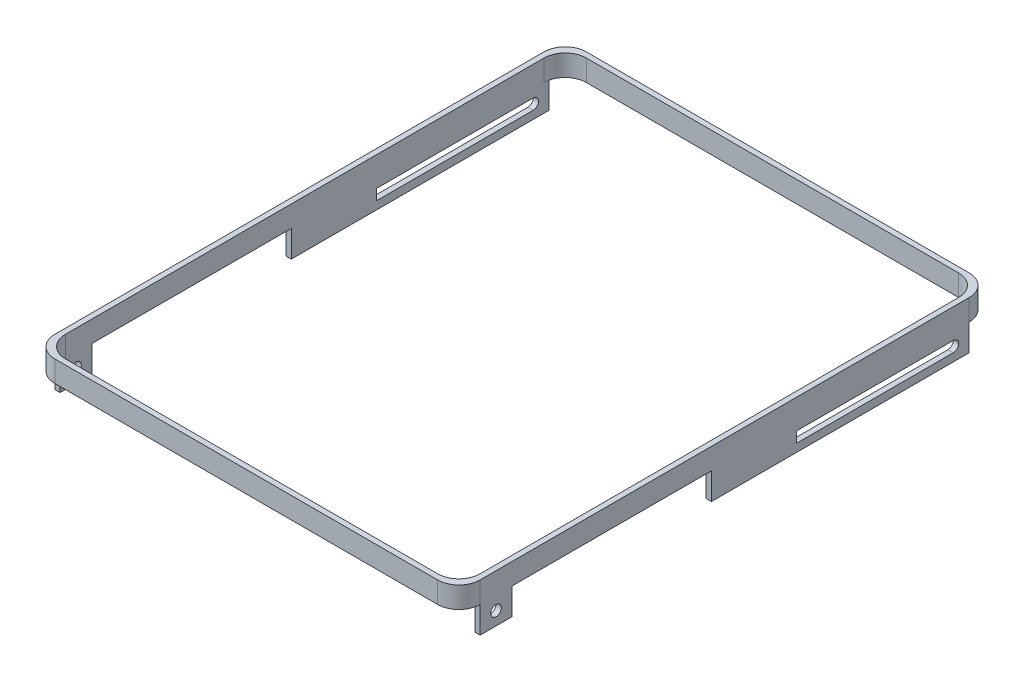
SolidWorks part; units mm, degrees
ref_plane "Front Plane" through (0, 0, 0) normal (0, 0, 1) x (1, 0, 0)
ref_plane "Top Plane" through (0, 0, 0) normal (0, 1, 0) x (1, 0, 0)
ref_plane "Right Plane" through (0, 0, 0) normal (1, 0, 0) x (0, 0, -1)
sketch "Sketch5" plane through (0, 0, 0) normal (0, 1, 0) x (1, 0, 0)
  line L1 (-180, 250) -> (180, 250)
  line L2 (-200, 230) -> (-200, -230)
  line L3 (-180, -250) -> (180, -250)
  line L4 (200, 230) -> (200, -230)
  line L5 (-200, 250) -> (200, -250) construction
  line L6 (-200, -250) -> (200, 250) construction
  arc A0 (-200, -230) -> (-180, -250) centre (-180, -230) ccw
  arc A1 (180, -250) -> (200, -230) centre (180, -230) ccw
  arc A2 (180, 250) -> (200, 230) centre (180, 230) cw
  arc A3 (-180, 250) -> (-200, 230) centre (-180, 230) ccw
  point P0 (0, 0)
  dimension "D3" = 20
  dimension "D1" = 500
  dimension "D2" = 400
extrude "Boss-Extrude2" add sketch "Sketch5" along normal blind 20
sketch "Sketch6" plane through (0, 20, 0) normal (0, 1, 0) x (1, 0, 0)
  line L1 (-175, -245) -> (175, -245)
  line L2 (-195, -225) -> (-195, 225)
  line L3 (-175, 245) -> (175, 245)
  line L4 (195, -225) -> (195, 225)
  line L5 (-195, -245) -> (195, 245) construction
  line L6 (-195, 245) -> (195, -245) construction
  arc A0 (-175, -245) -> (-195, -225) centre (-175, -225) cw
  arc A1 (175, -245) -> (195, -225) centre (175, -225) ccw
  arc A2 (175, 245) -> (195, 225) centre (175, 225) cw
  arc A3 (-195, 225) -> (-175, 245) centre (-175, 225) cw
  point P0 (0, 0)
  dimension "D3" = 20
  dimension "D1" = 490
  dimension "D2" = 390
extrude "Cut-Extrude1" cut sketch "Sketch6" against normal blind 20
sketch "Sketch7" plane through (200, 0, 0) normal (1, 0, 0) x (0, 0, -1)
  line L0 (230, 0) -> (230, -25)
  line L1 (230, -25) -> (-12.5565, -25)
  line L2 (-12.5565, -25) -> (-12.5565, 0)
  line L3 (-230, 0) -> (230, 0) construction
  line L4 (-12.5565, 0) -> (230, 0)
  dimension "D1" = 25
extrude "Boss-Extrude3" add sketch "Sketch7" against normal blind 5
sketch "Sketch8" plane through (-200, 0, 0) normal (-1, 0, 0) x (0, 0, 1)
  line L0 (-230, -25) -> (-230, 0) construction
  line L1 (12.5565, 0) -> (12.5565, -25) construction
  line L2 (12.5565, -25) -> (-230, -25) construction
  line L3 (-230, -25) -> (-230, 0)
  line L4 (12.5565, 0) -> (12.5565, -25)
  line L5 (12.5565, -25) -> (-230, -25)
  line L6 (-230, 0) -> (12.5565, 0)
extrude "Boss-Extrude4" add sketch "Sketch8" against normal blind 5
sketch "Sketch9" plane through (-200, 0, 0) normal (-1, 0, 0) x (0, 0, 1)
  line L0 (12.5565, 0) -> (-230, 0) construction
sketch "Sketch10" plane through (200, 0, 0) normal (1, 0, 0) x (0, 0, -1)
  line L10 (214.9751, -7.5) -> (2.4435, -7.5)
  line L13 (-12.5565, 0) -> (230, 0) construction
  line L15 (230, -25) -> (230, 0) construction
  line L16 (-12.5565, 0) -> (-12.5565, -25) construction
  line L18 (217.347, -16.9016) -> (215, -16.9016) construction
  line L20 (2.4435, -17.5) -> (214.9751, -17.5)
  arc A1 (2.4435, -7.5) -> (2.4435, -17.5) centre (2.4435, -12.5) ccw
  arc A3 (214.9751, -17.5) -> (214.9751, -7.5) centre (214.9751, -12.5) ccw
  dimension "D11" = 10
  dimension "D12" = 15.0249
  dimension "D14" = 5
  dimension "D13" = 15
  dimension "D15" = 212.5317
  dimension "D16" = 212.5317
extrude "Cut-Extrude2" cut sketch "Sketch10" against normal through all both and the other way through all
sketch "Sketch11" plane through (200, 0, 0) normal (1, 0, 0) x (0, 0, -1)
  line L0 (-230, 0) -> (-230, -25)
  line L1 (-230, -25) -> (-200, -25)
  line L2 (-200, -25) -> (-200, 0)
  line L3 (-230, 0) -> (-12.5565, 0) construction
  line L4 (-12.5565, -25) -> (-236.7643, -25) construction
  line L5 (-200, 0) -> (-230, 0)
  dimension "D1" = 30
  dimension "D2" = 25
extrude "Boss-Extrude5" add sketch "Sketch11" against normal blind 5
sketch "Sketch13" plane through (-200, 0, 0) normal (-1, 0, 0) x (0, 0, 1)
  line L0 (200, -25) -> (200, 0) construction
  line L1 (230, 0) -> (230, -25) construction
  line L2 (230, -25) -> (200, -25) construction
  line L3 (200, -25) -> (200, 0)
  line L4 (230, 0) -> (230, -25)
  line L5 (230, -25) -> (200, -25)
  line L6 (200, 0) -> (230, 0)
extrude "Boss-Extrude6" add sketch "Sketch13" against normal blind 5
sketch "Sketch14" plane through (-200, 0, 0) normal (-1, 0, 0) x (0, 0, 1)
  line L0 (-2.4435, -12.5) -> (215, -12.5) construction
  line L1 (230, -25) -> (230, 0) construction
  line L3 (12.5565, 0) -> (200, 0) construction
  line L5 (200, 0) -> (200, -25) construction
  line L6 (200, 0) -> (200, -25) construction
  circle A1 centre (215, -12.5) radius 5
  dimension "D2" = 10
  dimension "D1" = 15
extrude "Cut-Extrude3" cut sketch "Sketch14" against normal through all
sketch "Sketch16" plane through (-200, 0, 0) normal (-1, 0, 0) x (0, 0, 1)
  line L0 (-67.4435, -17.5) -> (-2.4435, -17.5)
  line L2 (-67.4435, -17.5) -> (-67.4435, -7.5)
  line L3 (-2.4435, -17.5) -> (-214.9751, -17.5) construction
  line L4 (-214.9751, -7.5) -> (-2.4435, -7.5) construction
  line L5 (-67.4435, -7.5) -> (-2.4435, -7.5)
  arc A0 (-2.4435, -17.5) -> (-2.4435, -7.5) centre (-2.4435, -12.5) ccw construction
  arc A1 (-2.4435, -17.5) -> (-2.4435, -7.5) centre (-2.4435, -12.5) ccw
extrude "Boss-Extrude7" add sketch "Sketch16" against normal blind 5
sketch "Sketch17" plane through (200, 0, 0) normal (1, 0, 0) x (0, 0, -1)
  line L0 (67.4435, -17.5) -> (67.4435, -7.5)
  line L1 (67.4435, -7.5) -> (2.4435, -7.5)
  line L2 (214.9751, -7.5) -> (2.4435, -7.5) construction
  line L3 (2.4435, -17.5) -> (67.4435, -17.5)
  line L4 (2.4435, -17.5) -> (214.9751, -17.5) construction
  arc A0 (2.4435, -7.5) -> (2.4435, -17.5) centre (2.4435, -12.5) ccw
extrude "Boss-Extrude8" add sketch "Sketch17" against normal blind 5
